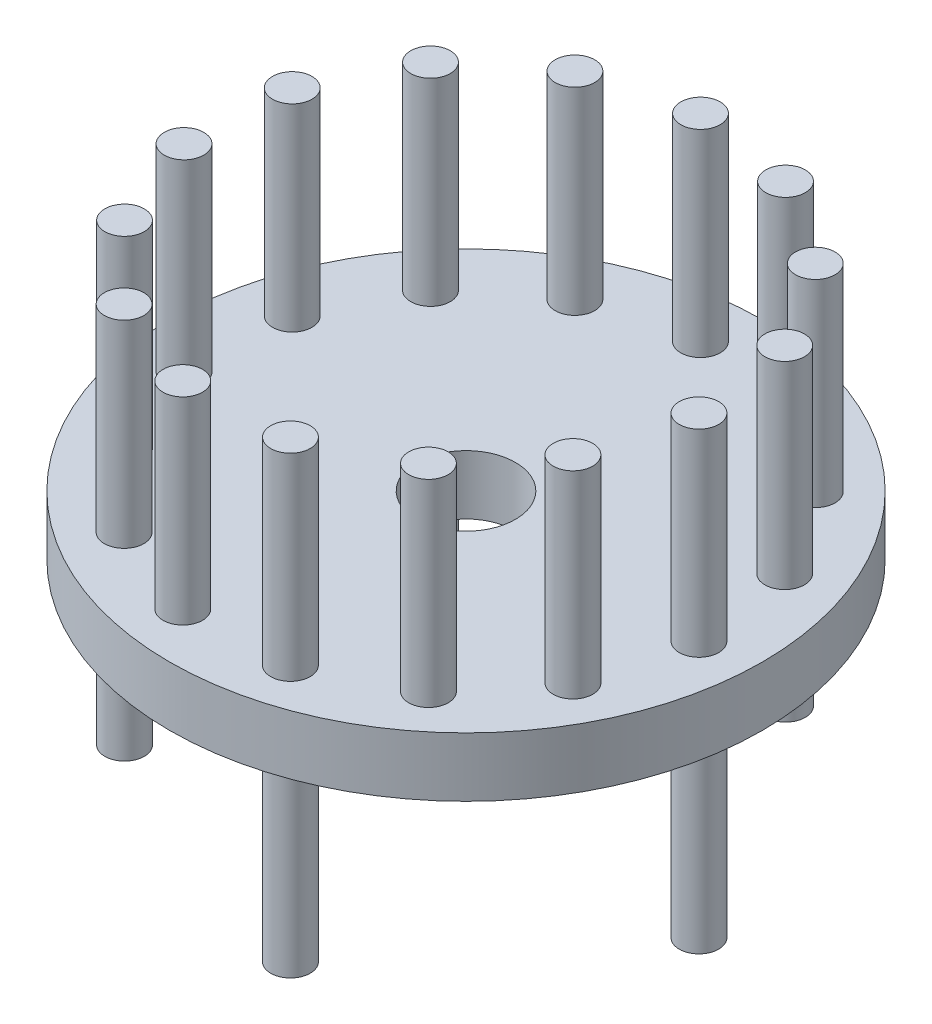
SolidWorks part; units mm, degrees
ref_plane "前基準面" through (0, 0, 0) normal (0, 0, 1) x (1, 0, 0)
ref_plane "上基準面" through (0, 0, 0) normal (0, 1, 0) x (1, 0, 0)
ref_plane "右基準面" through (0, 0, 0) normal (1, 0, 0) x (0, 0, -1)
sketch "草圖1" plane through (0, 0, 0) normal (0, 1, 0) x (1, 0, 0)
  circle A0 centre (0, 0) radius 15
  circle A1 centre (0, 0) radius 2.5
  dimension "D1" = 5
  dimension "D2" = 30
extrude "填料-伸長1" add sketch "草圖1" along normal blind 3
sketch "草圖2" plane through (0, 3, 0) normal (0, 1, 0) x (1, 0, 0)
  circle A0 centre (0, 0) radius 12.5 construction
  circle A1 centre (12.4809, -0.6912) radius 1
  dimension "D1" = 25
  dimension "D2" = 2
extrude "填料-伸長2" add sketch "草圖2" along normal blind 10
pattern_circular "環狀複製排列1" count 15 over 360 about axis through (0, 0, 0) along (0, 1, 0) of "填料-伸長2"
sketch "草圖3" plane through (0, 0, 0) normal (0, -1, 0) x (1, 0, 0)
  circle A0 centre (12.4809, 0.6912) radius 1
  dimension "D1" = 2
extrude "填料-伸長3" add sketch "草圖3" along normal blind 10
pattern_circular "環狀複製排列2" count 5 over 360 about axis through (0, 0, 0) along (0, 1, 0) of "填料-伸長3"
